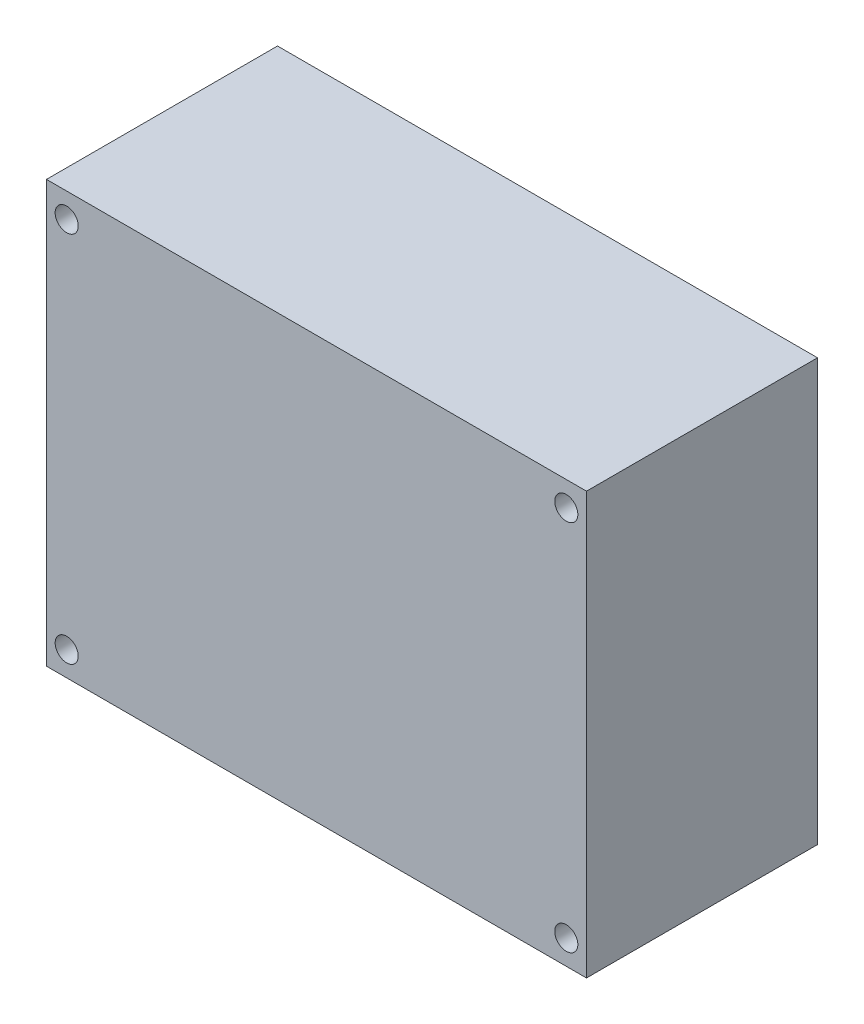
SolidWorks part; units mm, degrees
ref_plane "Ebene vorne" through (0, 0, 0) normal (0, 0, 1) x (1, 0, 0)
ref_plane "Ebene oben" through (0, 0, 0) normal (0, 1, 0) x (1, 0, 0)
ref_plane "Ebene rechts" through (0, 0, 0) normal (1, 0, 0) x (0, 0, -1)
sketch "Skizze1" plane through (0, 0, 0) normal (0, 0, 1) x (1, 0, 0)
  line L1 (-46.75, 36.5) -> (46.75, 36.5)
  line L2 (-46.75, 36.5) -> (-46.75, -36.5)
  line L3 (-46.75, -36.5) -> (46.75, -36.5)
  line L4 (46.75, 36.5) -> (46.75, -36.5)
  line L5 (-46.75, 36.5) -> (46.75, -36.5) construction
  line L6 (-46.75, -36.5) -> (46.75, 36.5) construction
  point P0 (0, 0)
  dimension "D1" = 93.5
  dimension "D2" = 73
extrude "Aufsatz-Linear austragen1" add sketch "Skizze1" along normal blind 40
sketch "Skizze2" plane through (0, 0, 40) normal (0, 0, 1) x (1, 0, 0)
  line L1 (43.25, 32.25) -> (-43.25, 32.25) construction
  line L2 (43.25, 32.25) -> (43.25, -32.25) construction
  line L3 (43.25, -32.25) -> (-43.25, -32.25) construction
  line L4 (-43.25, 32.25) -> (-43.25, -32.25) construction
  line L5 (43.25, 32.25) -> (-43.25, -32.25) construction
  line L6 (43.25, -32.25) -> (-43.25, 32.25) construction
  circle A0 centre (-43.25, 32.25) radius 2
  circle A1 centre (43.25, 32.25) radius 2
  circle A2 centre (43.25, -32.25) radius 2
  circle A3 centre (-43.25, -32.25) radius 2
  point P0 (0, 0)
  dimension "D1" = 4
  dimension "D2" = 86.5
  dimension "D3" = 64.5
extrude "Schnitt-Linear austragen1" cut sketch "Skizze2" against normal through all
